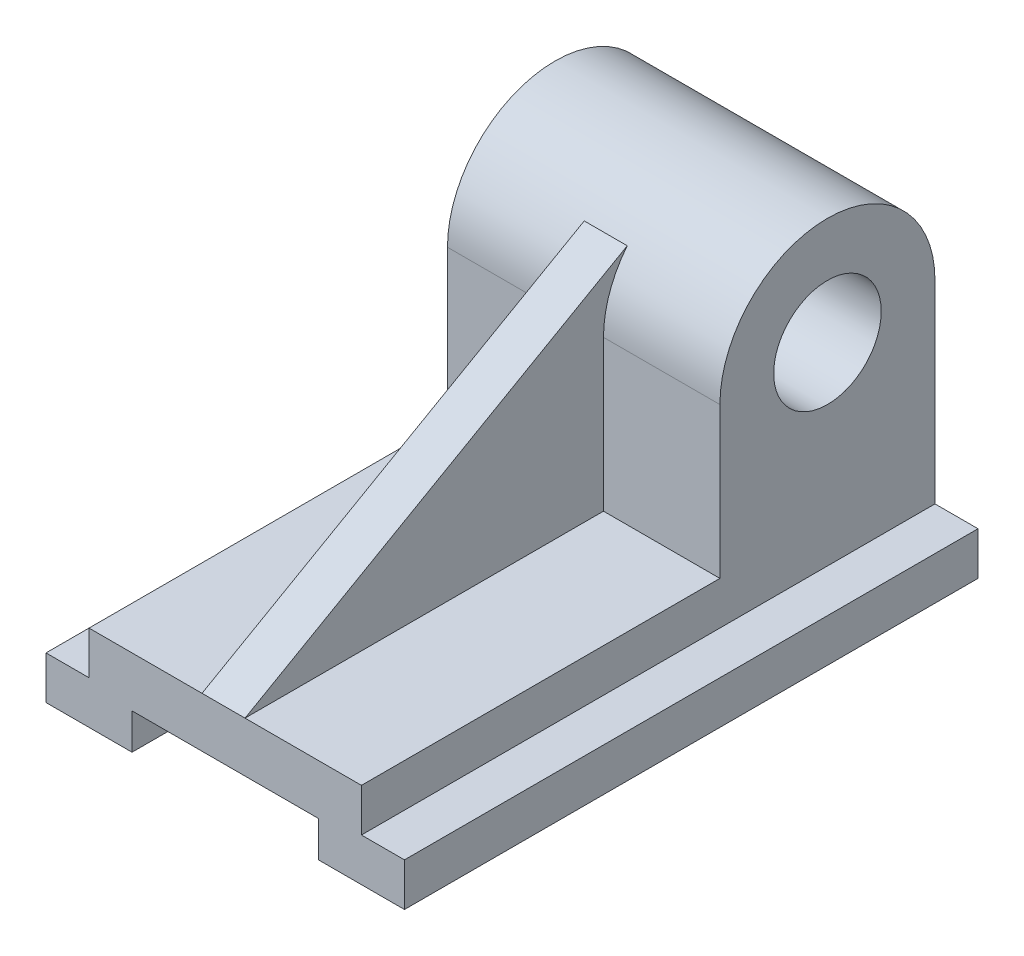
SolidWorks part; units mm, degrees
ref_plane "Front Plane" through (0, 0, 0) normal (0, 0, 1) x (1, 0, 0)
ref_plane "Top Plane" through (0, 0, 0) normal (0, 1, 0) x (1, 0, 0)
ref_plane "Right Plane" through (0, 0, 0) normal (1, 0, 0) x (0, 0, -1)
sketch "Sketch1" plane through (0, 0, 0) normal (0, 0, 1) x (1, 0, 0)
  line L0 (-43.5216, 0) -> (-43.5216, 12)
  line L1 (-43.5216, 12) -> (-31.5216, 12)
  line L2 (-31.5216, 12) -> (-31.5216, 24)
  line L3 (-31.5216, 24) -> (44.4784, 24)
  line L4 (44.4784, 24) -> (44.4784, 12)
  line L5 (44.4784, 12) -> (56.4784, 12)
  line L6 (56.4784, 12) -> (56.4784, 0)
  line L7 (56.4784, 0) -> (-43.5216, 0)
  line L8 (-19.5216, 0) -> (-19.5216, 10)
  line L9 (-19.5216, 10) -> (32.4784, 10)
  line L10 (32.4784, 10) -> (32.4784, 0)
  line L11 (32.4784, 0) -> (-19.5216, 0)
  line L12 (-43.5216, 0) -> (-19.5216, 0)
  line L13 (32.4784, 0) -> (56.4784, 0)
  point P10 (0, 0)
  point P13 (0, 0)
  point P14 (6.4784, 0)
  point P15 (6.4784, 10)
  dimension "D1" = 100
  dimension "D2" = 12
  dimension "D3" = 24
  dimension "D4" = 12
  dimension "D5" = 10
  dimension "D6" = 52
extrude "Boss-Extrude1" add sketch "Sketch1" against normal blind 160 contours L9 L10 L7 L6 L5 L4 L3 L2 L1 L0 L8
sketch "Sketch2" plane through (44.4784, 0, 0) normal (1, 0, 0) x (0, 0, -1)
  line L0 (160, 24) -> (160, 66)
  line L1 (100, 66) -> (100, 24)
  line L2 (160, 24) -> (0, 24) construction
  arc A0 (160, 66) -> (100, 66) centre (130, 66) ccw
  circle A1 centre (130, 66) radius 15
  line M5 (160, 24) -> (0, 24)
  dimension "D2" = 30
  dimension "D1" = 42
extrude "Boss-Extrude2" add sketch "Sketch2" against normal blind 76 contours L0 A0 L1 A1 M5
sketch "Sketch4" plane through (0, 24, 0) normal (0, 1, 0) x (1, 0, 0)
  line L1 (6.4784, 0) -> (6.4784, 100)
  line L2 (-31.5216, 100) -> (44.4784, 100) construction
sketch "Sketch8" plane through (0, 0, 0) normal (1, 0, 0) x (0, 0, -1)
  line L0 (0, 24) -> (109.6561, 86.5357)
  line L1 (109.6561, 86.5357) -> (109.6561, 24)
  line L2 (109.6561, 24) -> (0, 24)
  dimension "D1" = 109.6561
extrude "Boss-Extrude3" add sketch "Sketch8" along normal blind 12
